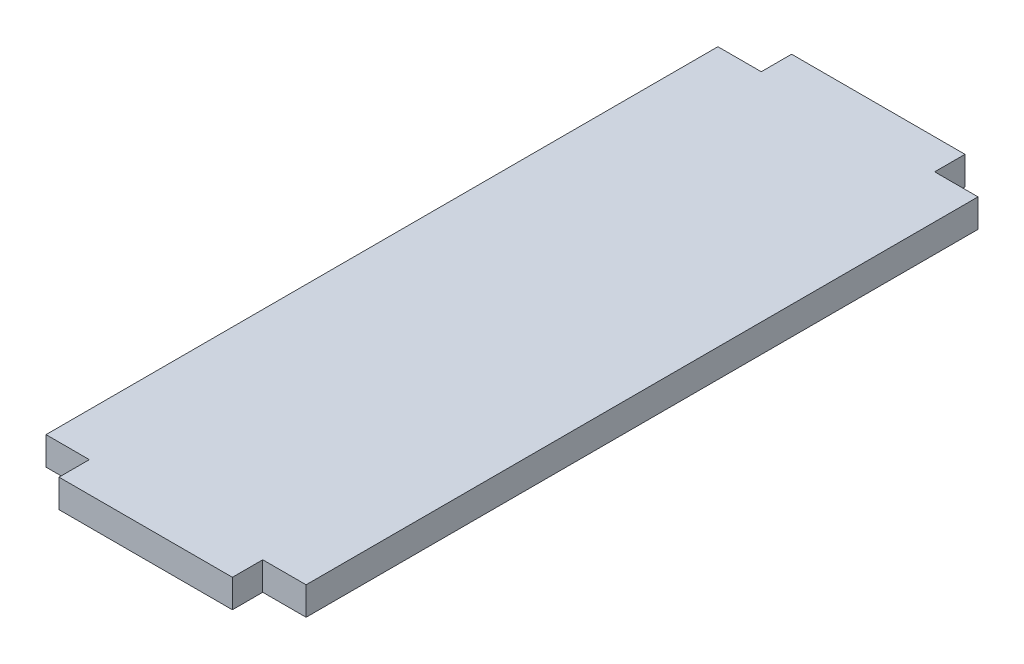
SolidWorks part; units mm, degrees
ref_plane "Front Plane" through (0, 0, 0) normal (0, 0, 1) x (1, 0, 0)
ref_plane "Top Plane" through (0, 0, 0) normal (0, 1, 0) x (1, 0, 0)
ref_plane "Right Plane" through (0, 0, 0) normal (1, 0, 0) x (0, 0, -1)
sketch "Sketch1" plane through (0, 0, 0) normal (0, 1, 0) x (1, 0, 0)
  line L1 (-6, 15.5) -> (6, 15.5)
  line L2 (-6, 15.5) -> (-6, -15.5)
  line L3 (-6, -15.5) -> (6, -15.5)
  line L4 (6, 15.5) -> (6, -15.5)
  line L5 (-6, 15.5) -> (6, -15.5) construction
  line L6 (-6, -15.5) -> (6, 15.5) construction
  point P0 (0, 0)
  dimension "D1" = 31
  dimension "D2" = 12
extrude "Boss-Extrude1" add sketch "Sketch1" along normal blind 1.3
sketch "Sketch2" plane through (0, 1.3, 0) normal (0, 1, 0) x (1, 0, 0)
  line L0 (6, 15.5) -> (-6, 15.5) construction
  line L1 (-4, 15.5) -> (4, 15.5)
  line L2 (-4, 15.5) -> (-4, 16.9)
  line L3 (-4, 16.9) -> (4, 16.9)
  line L4 (4, 15.5) -> (4, 16.9)
  line L12 (6, -15.5) -> (6, 15.5) construction
  line L13 (-0.715, 0) -> (0.715, 0) construction
  line L14 (-4, -15.5) -> (-4, -16.9)
  line L15 (-4, -15.5) -> (4, -15.5)
  line L16 (4, -15.5) -> (4, -16.9)
  line L17 (-4, -16.9) -> (4, -16.9)
  dimension "D1" = 8
  dimension "D4" = 1.4
  dimension "D5" = 2
extrude "Boss-Extrude2" add sketch "Sketch2" against normal blind 1.3
